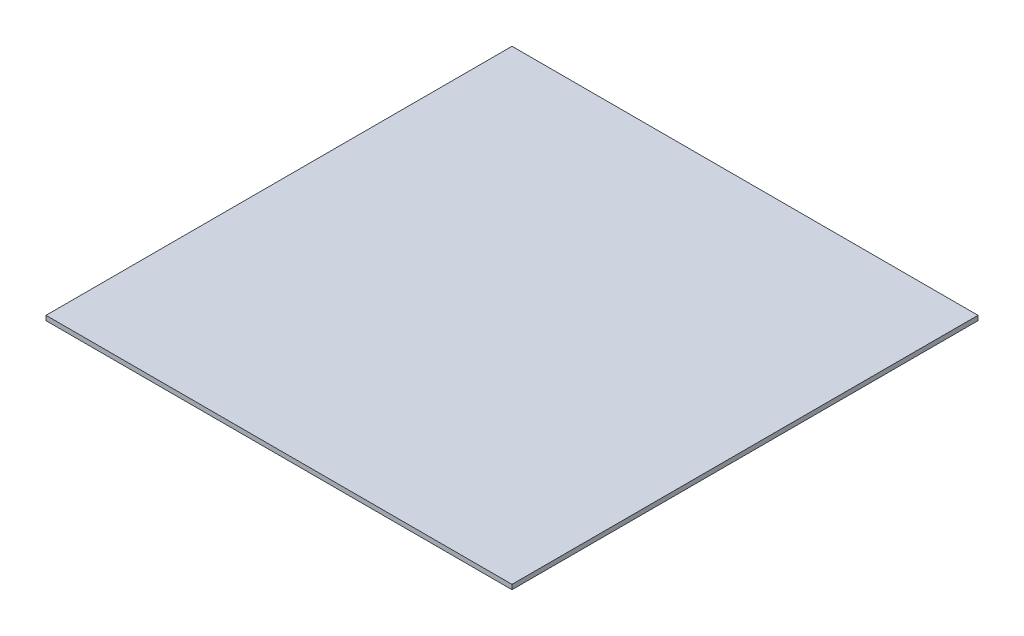
SolidWorks part; units mm, degrees
material "ABS"
ref_plane "Front Plane" through (0, 0, 0) normal (0, 0, 1) x (1, 0, 0)
ref_plane "Top Plane" through (0, 0, 0) normal (0, 1, 0) x (1, 0, 0)
ref_plane "Right Plane" through (0, 0, 0) normal (1, 0, 0) x (0, 0, -1)
sketch "Sketch1" plane through (0, 0, 0) normal (0, 1, 0) x (1, 0, 0)
  line L1 (-150, -150) -> (150, -150)
  line L2 (-150, -150) -> (-150, 150)
  line L3 (-150, 150) -> (150, 150)
  line L4 (150, -150) -> (150, 150)
  line L5 (-150, -150) -> (150, 150) construction
  line L6 (-150, 150) -> (150, -150) construction
  point P0 (0, 0)
extrude "Boss-Extrude1" add sketch "Sketch1" along normal blind 3
sketch "Sketch2" plane through (0, 0, 0) normal (0, 1, 0) x (1, 0, 0)
  line L0 (0, 165.8887) -> (0, -161.3911) construction
  line L1 (0, 0) -> (161.8699, 0) construction
  line L2 (161.8699, 0) -> (-160.9025, 0) construction
  line L3 (-149.6422, -149.9194) -> (149.8027, 149.5255) construction
  line L4 (150, -150) -> (-149.9655, 149.9655) construction
sketch "Sketch4" plane through (0, 0, 0) normal (1, 0, 0) x (0, 0, -1)
  line L0 (0, 0) -> (0, 13.5852) construction
